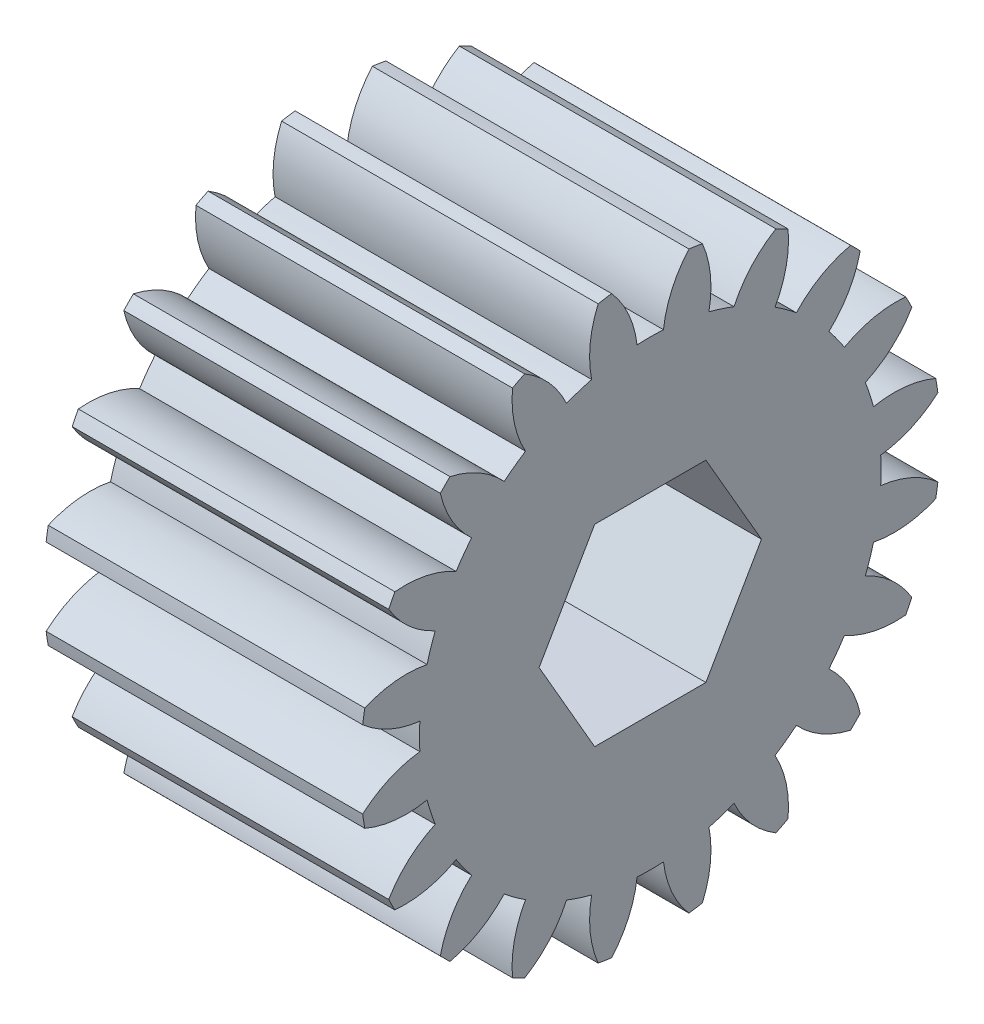
SolidWorks part; units mm, degrees
ref_plane "Plane1" through (0, 0, 0) normal (0, 0, 1) x (1, 0, 0)
ref_plane "Plane2" through (0, 0, 0) normal (0, 1, 0) x (1, 0, 0)
ref_plane "Plane3" through (0, 0, 0) normal (1, 0, 0) x (0, 0, -1)
other "Configuration Table"
sketch "HoldingSke" plane through (0, 0, 0) normal (0, 1, 0) x (1, 0, 0)
  line L0 (0, 0) -> (0.9397, -0.342)
  line L1 (-15, 0) -> (100, 0) construction
  line L2 (0, 0) -> (-2.1039, 2.3779)
  line L3 (0, 0) -> (-11.863, 4.5341)
  line L4 (0, 0) -> (8.1152, 2.9537)
  line L5 (0, 0) -> (-46.8476, -17.4728)
  line L6 (0, 0) -> (-9.9476, -6.7116)
  line L7 (-2.1039, 2.3779) -> (8.6586, 51.2059)
  line L8 (-76.2, 54.61) -> (-76.1, 54.61)
  line L9 (-71.009, 38.7566) -> (-53.1078, 45.2721)
  line L10 (-76.2, 71.12) -> (104.1128, 71.12)
  line L11 (0, 0) -> (-12, 0)
  line L12 (-76.2, 101.6) -> (-76.162, 101.6)
  line L13 (24.9733, 27.94) -> (52.9518, 28.4284)
  line L14 (24.9733, 27.94) -> (24.9743, 27.94)
  line L15 (24.9733, 27.94) -> (100.4006, 29.5858)
  line L16 (-63.627, -1) -> (-12.827, -1)
  circle A0 centre (0, 0) radius 0.4
  circle A1 centre (0, 0) radius 8.749
  circle A2 centre (0, 0) radius 37.5
  circle A3 centre (0, 0) radius 0.4
  dimension "MHD" = 17.498
  dimension "Hub_dia" = 75
  dimension "Bore" = 0.8
  dimension "MBD" = 0.8
  dimension "Num_teeth" = 20
  dimension "Pitch" = 1
  dimension "Overall_len" = 50
  dimension "Show_teeth" = 20
  dimension "Thickness" = 12
  dimension "OAL" = 50.0001
  dimension "T_dim" = 0.1
  dimension "Ap" = 20
  dimension "H" = 19.05
  dimension "Pitch_radius" = 180.3128
  dimension "Width" = 12
  dimension "Backlash" = 0.038
  dimension "Addendum_fac" = 1
  dimension "Dedendum_fac" = 1.25
  dimension "Clearance_fac" = 0.25
  dimension "Dedendum_add" = 0.001
  dimension "Module" = 1
sketch "BasProSke" plane through (0, 0, 0) normal (0, 1, 0) x (1, 0, 0)
  line L0 (-10, 0) -> (60, 0) construction
  line L1 (0, 0) -> (0, 11)
  line L2 (0, 0) -> (12, 0)
  line L3 (12, 0) -> (12, 11)
  line L4 (12, 11) -> (0, 11)
  dimension "Thickness" = 12
  dimension "Diameter" = 22
revolve "Base-Revolve" add sketch "BasProSke" angle 360 about L0
sketch "TooCutSke" plane through (0, 0, 0) normal (1, 0, 0) x (0, 0, -1)
  line L1 (0, 0) -> (0, 107) construction
  line L2 (0, 0) -> (-0.8511, 9.9637) construction
  line L3 (0, 0) -> (-3.1206, 19.7028) construction
  line L4 (-0.8511, 9.9637) -> (-1.5603, 9.8514) construction
  arc A0 (0.4999, 8.7347) -> (-0.4999, 8.7347) centre (0, 0) ccw
  arc A1 (1.4852, 10.9249) -> (-1.4852, 10.9249) centre (0, 0) ccw
  circle A2 centre (0, 0) radius 10 construction
  circle A3 centre (0, 0) radius 9.3969 construction
  arc A4 (-0.4999, 8.7347) -> (-1.4852, 10.9249) centre (-4.4722, 8.2645) ccw
  arc A5 (1.4852, 10.9249) -> (0.4999, 8.7347) centre (4.4722, 8.2645) ccw
  dimension "Root_dia" = 17.498
  dimension "Overcut_dia" = 22.0508
  dimension "Pitch_dia" = 20
  dimension "Base_dia" = 18.7939
  dimension "Flank_rad" = 4
  dimension "Half_ang" = 9
  dimension "Half_CT" = 0.7181
extrude "ToothCut" cut sketch "TooCutSke" along normal through all
fillet "Breaks" [suppressed] radius 0.02
fillet "RootFillets" [suppressed] radius 0.251
pattern_circular "TeethCuts" count 20 every 18 about axis through (-10, 0, 0) along (1, 0, 0) of "ToothCut", "RootFillets", "Breaks"
sketch "HubNeaOneSke" plane through (0, 0, 0) normal (-1, 0, 0) x (0, 0, 1)
  circle A0 centre (0, 0) radius 8.749
  dimension "Diameter" = 17.498
extrude "HubNearOne" [suppressed] add sketch "HubNeaOneSke" along normal blind 38.0001
sketch "HubNeaBotSke" plane through (0, 0, 0) normal (-1, 0, 0) x (0, 0, 1)
  circle A0 centre (0, 0) radius 8.749
  dimension "Diameter" = 17.498
extrude "HubNearBoth" [suppressed] add sketch "HubNeaBotSke" along normal blind 19
ref_plane "FarPln" through (12, 0, 0) normal (1, 0, 0) x (0, 0, -1)
sketch "HubFarSke" plane through (12, 0, 0) normal (1, 0, 0) x (0, 0, -1)
  circle A0 centre (0, 0) radius 8.749
  dimension "Diameter" = 17.498
extrude "HubFar" [suppressed] add sketch "HubFarSke" along normal blind 19
sketch "BorSke" plane through (0, 0, 0) normal (1, 0, 0) x (0, 0, -1)
  circle A0 centre (0, 0) radius 0.4
  dimension "Diameter" = 0.8
extrude "Bore" cut sketch "BorSke" along normal mid plane 100.0001
sketch "KeySke" plane through (0, 0, 0) normal (1, 0, 0) x (0, 0, -1)
  line L0 (-0.05, 0) -> (-0.05, 0.5)
  line L1 (-0.05, 0.5) -> (0.05, 0.5)
  line L2 (0.05, 0.5) -> (0.05, 0)
  line L3 (0, 0) -> (0, 34) construction
  line L4 (-0.05, 0) -> (0.05, 0)
  dimension "Offset" = 0.5
  dimension "Width" = 0.1
extrude "Keyway" [suppressed] cut sketch "KeySke" along normal mid plane 100.0001
pattern_circular "Keyway2" [suppressed] count 2 every 90 about axis through (-10, 0, 0) along (1, 0, 0)
sketch "Çizim1" plane through (12, 0, 0) normal (1, 0, 0) x (0, 0, -1)
  line L1 (4.2147, 0) -> (2.1073, 3.65)
  line L2 (2.1073, 3.65) -> (-2.1073, 3.65)
  line L3 (-2.1073, 3.65) -> (-4.2147, 0)
  line L4 (-4.2147, 0) -> (-2.1073, -3.65)
  line L5 (-2.1073, -3.65) -> (2.1073, -3.65)
  line L6 (2.1073, -3.65) -> (4.2147, 0)
  circle A0 centre (0, 0) radius 3.65 construction
  dimension "D1" = 7.3
extrude "Kes-Ekstrüzyon1" cut sketch "Çizim1" against normal blind 20
equation "' \"Module@HoldingSke\" = 6.35"
equation "' \"Num_teeth@HoldingSke\" = 12"
equation "' \"Ap@HoldingSke\" =  20"
equation "' \"Ap@HoldingSke\" = 20"
equation "' \"Width@HoldingSke\" = 0.5 * 25.4"
equation "' \"Hub_dia@HoldingSke\"= 1 * 25.4"
equation "' \"Hub_dia@HoldingSke\" = 1 * 25.4"
equation "' \"Overall_len@HoldingSke\" = 1.0 * 25.4"
equation "' \"Bore@HoldingSke\" = 0.75 * 25.4"
equation "' \"T_dim@HoldingSke\" = 0.1 * 25.4"
equation "' \"Width@KeySke\" = 0.25 * 25.4"
equation "' \"Show_teeth@HoldingSke\" = 13"
equation "' \"Backlash@HoldingSke\" = 0.009 * 25.4"
equation "' \"Addendum_fac@HoldingSke\" = 1.0"
equation "' \"Dedendum_fac@HoldingSke\" = 1.25"
equation "' \"Dedendum_add@HoldingSke\" = 0.00005 * 25.4"
equation "' \"Clearance_fac@HoldingSke\" = 0.25"
equation "\"Pitch@HoldingSke\" = 1 / \"Module@HoldingSke\""
equation "\"Overcut_dia@TooCutSke\" = (\"Num_teeth@HoldingSke\" + 2 * \"Addendum_fac@HoldingSke\") / \"Pitch@HoldingSke\" + 0.002 * 25.4"
equation "\"Pitch_dia@TooCutSke\" = \"Num_teeth@HoldingSke\" / \"Pitch@HoldingSke\""
equation "\"Base_dia@TooCutSke\" = \"Num_teeth@HoldingSke\" / \"Pitch@HoldingSke\" * cos((\"Ap@HoldingSke\"  * 3.14159265 / 180))"
equation "\"Root_dia@TooCutSke\" = (\"Num_teeth@HoldingSke\" + 2) / \"Pitch@HoldingSke\" - 2 * (\"Addendum_fac@HoldingSke\" + \"Dedendum_fac@HoldingSke\") / \"Pitch@HoldingSke\" - \"Dedendum_add@HoldingSke\" * 2"
equation "\"Half_ang@TooCutSke\" = 180 / \"Num_teeth@HoldingSke\""
equation "\"Half_CT@TooCutSke\" = \"Num_teeth@HoldingSke\" / \"Pitch@HoldingSke\" * sin((3.14159265 / 2 / \"Num_teeth@HoldingSke\")) / 2 - 7 * \"Backlash@HoldingSke\" / 4"
equation "\"Flank_rad@TooCutSke\" = \"Num_teeth@HoldingSke\" / \"Pitch@HoldingSke\" / 5"
equation "\"Radius@RootFillets\" = \"Clearance_fac@HoldingSke\" / \"Pitch@HoldingSke\" + \"Dedendum_add@HoldingSke\""
equation "\"Break_rad@Breaks\" = 0.02 / \"Pitch@HoldingSke\""
equation "\"Thickness@HoldingSke\" = \"Width@HoldingSke\""
equation "\"OAL@HoldingSke\" = \"Thickness@HoldingSke\""
equation "\"MHD@HoldingSke\" = (\"Num_teeth@HoldingSke\" + 2) / \"Pitch@HoldingSke\" - 2 * (\"Addendum_fac@HoldingSke\" + \"Dedendum_fac@HoldingSke\")  / \"Pitch@HoldingSke\" - \"Dedendum_add@HoldingSke\" * 2"
equation "\"MBD@HoldingSke\" = (\"Num_teeth@HoldingSke\" + 2) / \"Pitch@HoldingSke\" - 2 * (\"Addendum_fac@HoldingSke\" + \"Dedendum_fac@HoldingSke\")  / \"Pitch@HoldingSke\" - \"Dedendum_add@HoldingSke\" * 2 - 0.002 * 25.4"
equation "\"MHD@HoldingSke\" = ((sgn( \"MHD@HoldingSke\" - \"Hub_dia@HoldingSke\" )-1)*( \"MHD@HoldingSke\" - \"Hub_dia@HoldingSke\" ))/-2+ \"Hub_dia@HoldingSke\""
equation "\"MBD@HoldingSke\" = ((sgn( \"MBD@HoldingSke\" - \"Bore@HoldingSke\" )-1)*( \"MBD@HoldingSke\" - \"Bore@HoldingSke\" ))/-2+ \"Bore@HoldingSke\""
equation "\"OAL@HoldingSke\" = ((sgn( \"OAL@HoldingSke\" - \"Overall_len@HoldingSke\" )+1)*( \"OAL@HoldingSke\" - \"Overall_len@HoldingSke\" ))/2 + \"Overall_len@HoldingSke\" + 0.000002 * 25.4"
equation "\"Num_teeth@TeethCuts\" = int( \"Show_teeth@HoldingSke\" ) + 1"
equation "\"Num_teeth@TeethCuts\" = ((sgn( \"Num_teeth@TeethCuts\" - \"Num_teeth@HoldingSke\" )-1)*( \"Num_teeth@TeethCuts\" - \"Num_teeth@HoldingSke\" ))/-2+ \"Num_teeth@HoldingSke\""
equation "\"Num_teeth@TeethCuts\" = ((sgn( \"Num_teeth@TeethCuts\" - 2.0)+1)*( \"Num_teeth@TeethCuts\" - 2.0))/2 +2.0"
equation "\"Angle@TeethCuts\" = 360.0 / \"Num_teeth@HoldingSke\""
equation "\"Diameter@BasProSke\" = (\"Num_teeth@HoldingSke\" + 2 * \"Addendum_fac@HoldingSke\") / \"Pitch@HoldingSke\""
equation "\"Thickness@BasProSke\"  = \"Thickness@HoldingSke\""
equation "' \"Fillet_rad@BasProSke\" =  \"Thickness@HoldingSke\" * 0.05"
equation "' \"Fillet_rad@BasProSke\" = \"Thickness@HoldingSke\" * 0.05"
equation "\"MHD@HoldingSke\" = ((sgn( \"MHD@HoldingSke\" - \"Root_dia@TooCutSke\" )-1)*( \"MHD@HoldingSke\" - \"Root_dia@TooCutSke\" ))/-2+ \"Root_dia@TooCutSke\""
equation "\"Diameter@HubNeaOneSke\" = \"MHD@HoldingSke\""
equation "\"Length@HubNearOne\" = \"OAL@HoldingSke\" - \"Thickness@BasProSke\""
equation "\"Diameter@HubNeaBotSke\" = \"MHD@HoldingSke\""
equation "\"Length@HubNearBoth\" = ( \"OAL@HoldingSke\" - \"Thickness@BasProSke\" ) / 2.0"
equation "\"Thickness@FarPln\" = \"Thickness@BasProSke\""
equation "\"Diameter@HubFarSke\" = \"MHD@HoldingSke\""
equation "\"Length@HubFar\" = ( \"OAL@HoldingSke\" - \"Thickness@BasProSke\" ) / 2.0"
equation "\"Diameter@BorSke\" = \"MBD@HoldingSke\""
equation "\"D1@Bore\" = \"OAL@HoldingSke\" * 2.0"
equation "\"D1@Keyway\" = \"OAL@HoldingSke\" * 2.0"
equation "\"Offset@KeySke\" = \"T_dim@HoldingSke\" + \"MBD@HoldingSke\" / 2.0"
